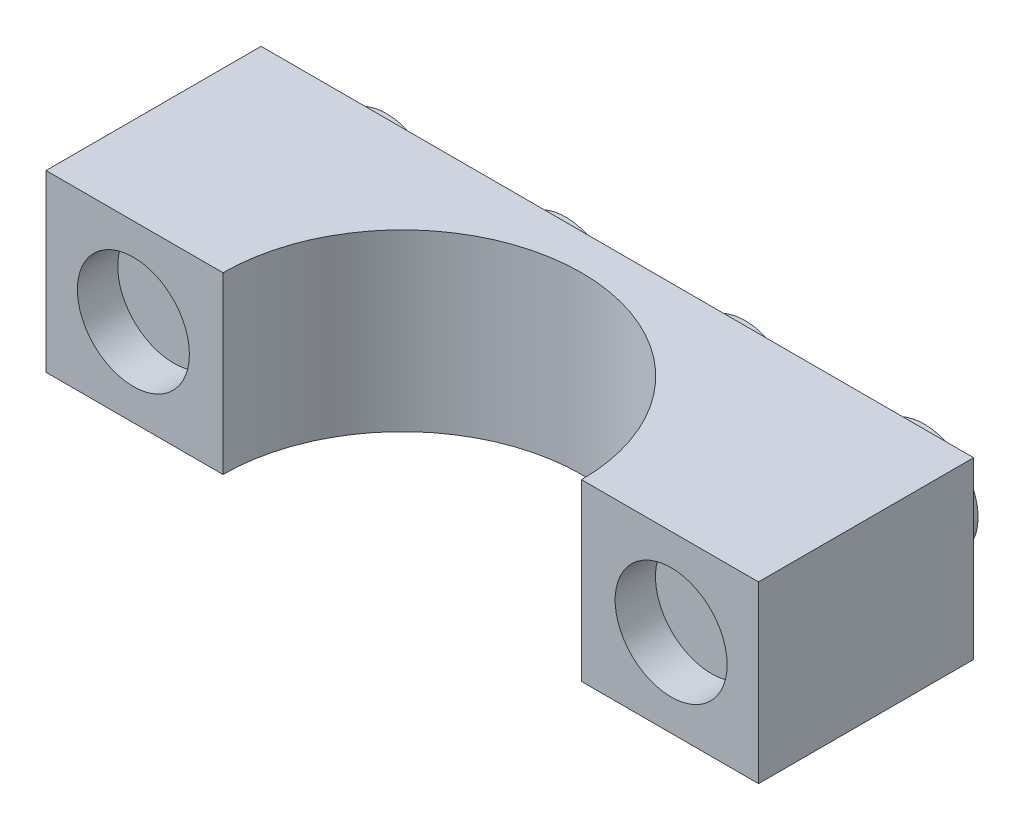
SolidWorks part; units mm, degrees
ref_plane "Спереди" through (0, 0, 0) normal (0, 0, 1) x (1, 0, 0)
ref_plane "Сверху" through (0, 0, 0) normal (0, 1, 0) x (1, 0, 0)
ref_plane "Справа" through (0, 0, 0) normal (1, 0, 0) x (0, 0, -1)
sketch "Эскиз1" plane through (0, 0, 0) normal (0, 0, 1) x (1, 0, 0)
  line L1 (-15.9, -3.9) -> (15.9, -3.9)
  line L2 (-15.9, -3.9) -> (-15.9, 3.9)
  line L3 (-15.9, 3.9) -> (15.9, 3.9)
  line L4 (15.9, -3.9) -> (15.9, 3.9)
  line L5 (-15.9, -3.9) -> (15.9, 3.9) construction
  line L6 (-15.9, 3.9) -> (15.9, -3.9) construction
  point P0 (0, 0)
  dimension "D1" = 31.8
  dimension "D2" = 7.8
extrude "Бобышка-Вытянуть2" add sketch "Эскиз1" along normal blind 9.6
sketch "Эскиз2" plane through (0, 0, 0) normal (0, 0, -1) x (-1, 0, 0)
  line L0 (-15.9, 3.9) -> (15.9, 3.9) construction
  line L1 (-15.9, -3.9) -> (-15.9, 3.9) construction
  circle A0 centre (-12, 0) radius 2.4
  circle A3 centre (-4, 0) radius 2.4
  circle A4 centre (4, 0) radius 2.4
  circle A5 centre (12, 0) radius 2.4
  dimension "D1" = 3.9
  dimension "D2" = 3.9
  dimension "D3" = 4
extrude "Бобышка-Вытянуть3" add sketch "Эскиз2" along normal blind 1.7
sketch "Эскиз3" plane through (0, -3.9, 0) normal (0, -1, 0) x (1, 0, 0)
  line L0 (-15.9, 0) -> (15.9, 0) construction
  line L1 (8, 0) -> (-8, 0)
  line L3 (8, 9.6) -> (-8, 9.6)
  line L5 (-15.9, 9.6) -> (15.9, 9.6) construction
  arc A0 (-8, 9.6) -> (8, 9.6) centre (0, 9.6) ccw
extrude "Вырез-Вытянуть2" cut sketch "Эскиз3" against normal through all contours L3 A0
sketch "Эскиз4" plane through (0, 0, 9.6) normal (0, 0, 1) x (1, 0, 0)
  line L0 (8, -3.9) -> (15.9, -3.9) construction
  line L2 (15.9, -3.9) -> (15.9, 3.9) construction
  line L3 (-15.9, -3.9) -> (-8, -3.9) construction
  line L4 (-15.9, 3.9) -> (-15.9, -3.9) construction
  circle A0 centre (12, 0) radius 2.5
  circle A1 centre (-12, 0) radius 2.5
  point P8 (0, 0)
  dimension "D1" = 3.9
  dimension "D2" = 3.9
  dimension "D3" = 3.9
  dimension "D4" = 3.9
extrude "Вырез-Вытянуть3" cut sketch "Эскиз4" against normal blind 1.8
